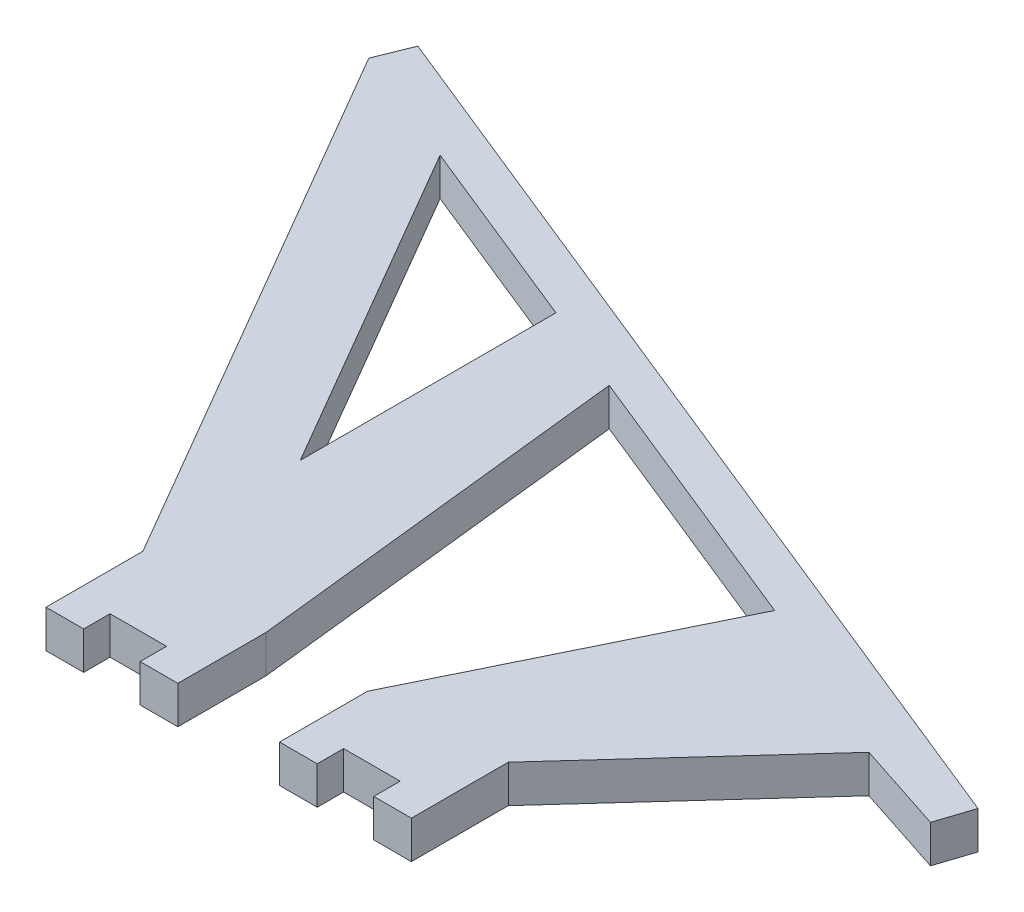
SolidWorks part; units mm, degrees
ref_plane "Front Plane" through (0, 0, 0) normal (0, 0, 1) x (1, 0, 0)
ref_plane "Top Plane" through (0, 0, 0) normal (0, 1, 0) x (1, 0, 0)
ref_plane "Right Plane" through (0, 0, 0) normal (1, 0, 0) x (0, 0, -1)
sketch "Sketch1" plane through (0, 0, 0) normal (0, 1, 0) x (1, 0, 0)
  line L2 (13.5, -3.126) -> (13.5, 3.126)
  line L4 (-13.5, -3.126) -> (-13.5, 3.126)
  line L5 (-24.7371, 115.6264) -> (-13.5, 13.2147)
  line L6 (48.9713, 85.829) -> (-24.7371, 115.6264)
  line L7 (-23.5, -3.126) -> (-38.5, -3.126)
  line L8 (-13.5, -3.126) -> (-13.5, 13.2147)
  line L10 (-48.5, -3.126) -> (-48.5, 15.6034)
  line L11 (23.5, -3.126) -> (38.5, -3.126)
  line L12 (13.5, -3.126) -> (13.5, 13.2147)
  line L14 (48.5, -3.126) -> (48.5, 15.6034)
  line L16 (-48.5, -3.126) -> (-48.5, -10.1282)
  line L17 (-48.5, -10.1282) -> (-38.5, -10.1282)
  line L18 (-38.5, -3.126) -> (-38.5, -10.1282)
  line L20 (-13.5, -3.126) -> (-13.5, -10.1282)
  line L21 (-13.5, -10.1282) -> (-23.5, -10.1282)
  line L22 (-23.5, -3.126) -> (-23.5, -10.1282)
  line L24 (13.5, -3.126) -> (13.5, -10.1282)
  line L25 (13.5, -10.1282) -> (23.5, -10.1282)
  line L26 (23.5, -3.126) -> (23.5, -10.1282)
  line L28 (48.5, -3.126) -> (48.5, -10.1282)
  line L29 (48.5, -10.1282) -> (38.5, -10.1282)
  line L30 (38.5, -3.126) -> (38.5, -10.1282)
  line L31 (13.5, 13.2147) -> (48.9713, 85.829)
  line L33 (0, -55) -> (0, 55) construction
  line L35 (-48.5, 125.2328) -> (-98.6887, 145.5222)
  line L38 (94.0826, 65.7454) -> (48.5, 15.6034)
  line L42 (94.0826, 65.7454) -> (118.3646, 57.8009)
  line L43 (118.3646, 57.8009) -> (121.4741, 67.3051)
  line L44 (121.4741, 67.3051) -> (-128.1255, 168.2085)
  line L45 (-128.1255, 168.2085) -> (-131.8734, 158.9374)
  line L46 (-100.1101, 146.0968) -> (-98.6887, 145.5222)
  line L47 (-48.5, 15.6034) -> (-131.8734, 158.9374)
  line L50 (-48.5, 125.2328) -> (-48.5, 57.3696)
  line L51 (-48.5, 57.3696) -> (-100.1101, 146.0968)
  point P0 (0, 0)
  point P9 (0, 0)
  point P25 (0, 0)
  point P26 (-23.5, -6.6271)
  point P27 (0, 0)
  point P28 (0, 0)
  point P31 (0, 0)
  point P33 (-48.5, 14.4937)
  point P44 (-48.5, 15.6034)
  point P45 (0, 0)
  dimension "D2" = 15
  dimension "D3" = 35
  dimension "D4" = 10
  dimension "D5" = 10
  dimension "D6" = 10
  dimension "D7" = 27
  dimension "D8" = 34.2606
  dimension "D9" = 25.6312
  dimension "D10" = 10
  dimension "D11" = 10
  dimension "D12" = 10
  dimension "D13" = 10
  dimension "D14" = 10
  dimension "D16" = 21
extrude "Boss-Extrude1" add sketch "Sketch1" along normal blind 10
